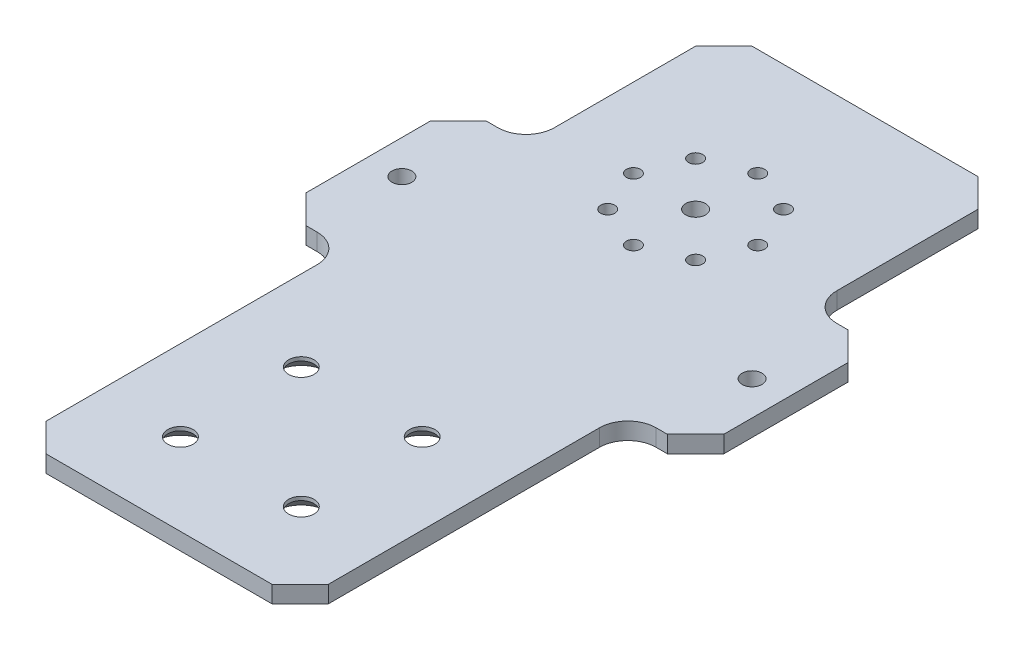
SolidWorks part; units mm, degrees
material "3003 Alloy"
ref_plane "Front Plane" through (0, 0, 0) normal (0, 0, 1) x (1, 0, 0)
ref_plane "Top Plane" through (0, 0, 0) normal (0, 1, 0) x (1, 0, 0)
ref_plane "Right Plane" through (0, 0, 0) normal (1, 0, 0) x (0, 0, -1)
sketch "Sketch1" plane through (0, 0, 0) normal (0, 1, 0) x (1, 0, 0)
  line L0 (0, 62.5) -> (0, 0) construction
  line L1 (-25, 62.5) -> (25, 62.5)
  line L2 (-25, 62.5) -> (-25, -62.5)
  line L3 (-25, -62.5) -> (25, -62.5)
  line L4 (25, 62.5) -> (25, -62.5)
  line L5 (0, 0) -> (25, 0) construction
  dimension "D1" = 125
  dimension "D2" = 50
extrude "Boss-Extrude1" add sketch "Sketch1" along normal blind 3
sketch "Sketch2" plane through (0, 3, 0) normal (0, 1, 0) x (1, 0, 0)
  line L0 (0, -62.5) -> (0, 32.5) construction
  line L1 (-25, -62.5) -> (25, -62.5) construction
  line L2 (25, 62.5) -> (-25, 62.5) construction
  circle A0 centre (0, 32.5) radius 1.75
  dimension "D1" = 3.5
  dimension "D2" = 30
extrude "Cut-Extrude1" cut sketch "Sketch2" against normal blind 10
sketch "Sketch14" plane through (0, 3, 0) normal (0, 1, 0) x (1, 0, 0)
  line L0 (0, -26.6) -> (0, -48) construction
  line L1 (-10.7, -26.6) -> (10.7, -26.6) construction
  line L2 (-10.7, -26.6) -> (-10.7, -48) construction
  line L3 (-10.7, -48) -> (10.7, -48) construction
  line L4 (10.7, -26.6) -> (10.7, -48) construction
  line L5 (-10.7, -37.3) -> (0, -37.3) construction
  line L6 (-25, -62.5) -> (25, -62.5) construction
  line L7 (0, -48) -> (0, -62.5) construction
  circle A0 centre (-10.7, -26.6) radius 2
  circle A1 centre (10.7, -26.6) radius 2
  circle A2 centre (10.7, -48) radius 2
  circle A3 centre (-10.7, -48) radius 2
  dimension "D3" = 4
  dimension "D1" = 21.4
  dimension "D2" = 21.4
  dimension "D4" = 14.5
extrude "Cut-Extrude16" cut sketch "Sketch14" against normal blind 10
hole_wizard "CSK for M4 Hex Socket Countersunk Head Screw1" positions "3DSketch3" profile "Sketch15" countersink size "M4" standard "DIN" end condition through all
sketch3d "3DSketch3"
  line L0 (-10.7, 0, 26.6) -> (-10.7, 3, 26.6) construction
  line L1 (10.7, 0, 26.6) -> (10.7, 3, 26.6) construction
  line L2 (10.7, 0, 48) -> (10.7, 3, 48) construction
  line L3 (-10.7, 0, 48) -> (-10.7, 3, 48) construction
  point P0 (-10.7, 0, 26.6)
  point P4 (10.7, 0, 26.6)
  point P8 (10.7, 0, 48)
  point P12 (-10.7, 0, 48)
sketch "Sketch15" plane through (-10.7, 0, 26.6) normal (1, 0, 0) x (0, 0, -1)
  line L0 (0, 0) -> (0, 3)
  line L1 (0, 3) -> (2.25, 3)
  line L2 (2.25, 3) -> (2.25, 2.34)
  line L3 (2.25, 2.34) -> (4.59, 0)
  line L5 (4.59, 0) -> (0, 0)
  line L6 (-2.25, 2.34) -> (-4.59, 0) construction
  line L11 (0, -6.35) -> (0, 107.95) construction
  dimension "Thru Hole Dia." = 4.5
  dimension "Thru Hole Depth" = 3
  dimension "Near C'Sink Dia." = 9.18
  dimension "Near C'Sink Angle" = 90
sketch "Sketch18" plane through (0, 0, 0) normal (0, -1, 0) x (1, 0, 0)
  circle A0 centre (0, -21.5) radius 1.25
  circle A1 centre (0, -43.5) radius 1.25
  circle A2 centre (-11, -32.5) radius 1.25
  circle A3 centre (11, -32.5) radius 1.25
  circle A4 centre (7.7782, -24.7218) radius 1.25
  circle A5 centre (-7.7782, -24.7218) radius 1.25
  circle A6 centre (-7.7782, -40.2782) radius 1.25
  circle A7 centre (7.7782, -40.2782) radius 1.25
  dimension "D1" = 2.5
extrude "Cut-Extrude17" cut sketch "Sketch18" against normal up to next
chamfer "Chamfer1" distance 5 angle 45 4 edges at (25, 1.5, -62.5) (25, 1.5, 62.5) (-25, 1.5, 62.5) (-25, 1.5, -62.5)
sketch "Sketch19" plane through (0, 3, 0) normal (0, 1, 0) x (1, 0, 0)
  line L0 (-25, 57.5) -> (-25, -57.5) construction
  line L1 (-25, 27.5) -> (-37, 27.5)
  line L2 (-25, 27.5) -> (-25, -4.5)
  line L3 (-25, -4.5) -> (-37, -4.5)
  line L4 (-37, 27.5) -> (-37, -4.5)
  line L5 (0, 62.5) -> (0, -62.5) construction
  line L6 (20, 62.5) -> (-20, 62.5) construction
  line L7 (-20, -62.5) -> (20, -62.5) construction
  line L8 (37, 27.5) -> (37, -4.5)
  line L9 (25, -4.5) -> (37, -4.5)
  line L10 (25, 27.5) -> (25, -4.5)
  line L11 (25, 27.5) -> (37, 27.5)
  dimension "D1" = 35
  dimension "D2" = 12
  dimension "D3" = 32
extrude "Boss-Extrude2" add sketch "Sketch19" against normal up to surface (3 mm away) up to face at (7.7782, 0, -41.5282)
chamfer "Chamfer2" distance 5 angle 45 4 edges at (37, 1.5, -27.5) (37, 1.5, 4.5) (-37, 1.5, -27.5) (-37, 1.5, 4.5)
fillet "Fillet1" radius 5 4 edges
sketch "Sketch20" plane through (0, 3, 0) normal (0, 1, 0) x (1, 0, 0)
  line L0 (-37, 11.5) -> (-25, 11.5) construction
  line L1 (-37, 22.5) -> (-37, 0.5) construction
  line L2 (-25, 11.5) -> (-25, 32.5) construction
  line L3 (0, 62.5) -> (0, 0) construction
  line L4 (20, 62.5) -> (-20, 62.5) construction
  circle A0 centre (-31, 11.5) radius 1.75
  circle A1 centre (0, 32.5) radius 1.75 construction
  circle A2 centre (31, 11.5) radius 1.75
extrude "Cut-Extrude18" cut sketch "Sketch20" against normal through all
